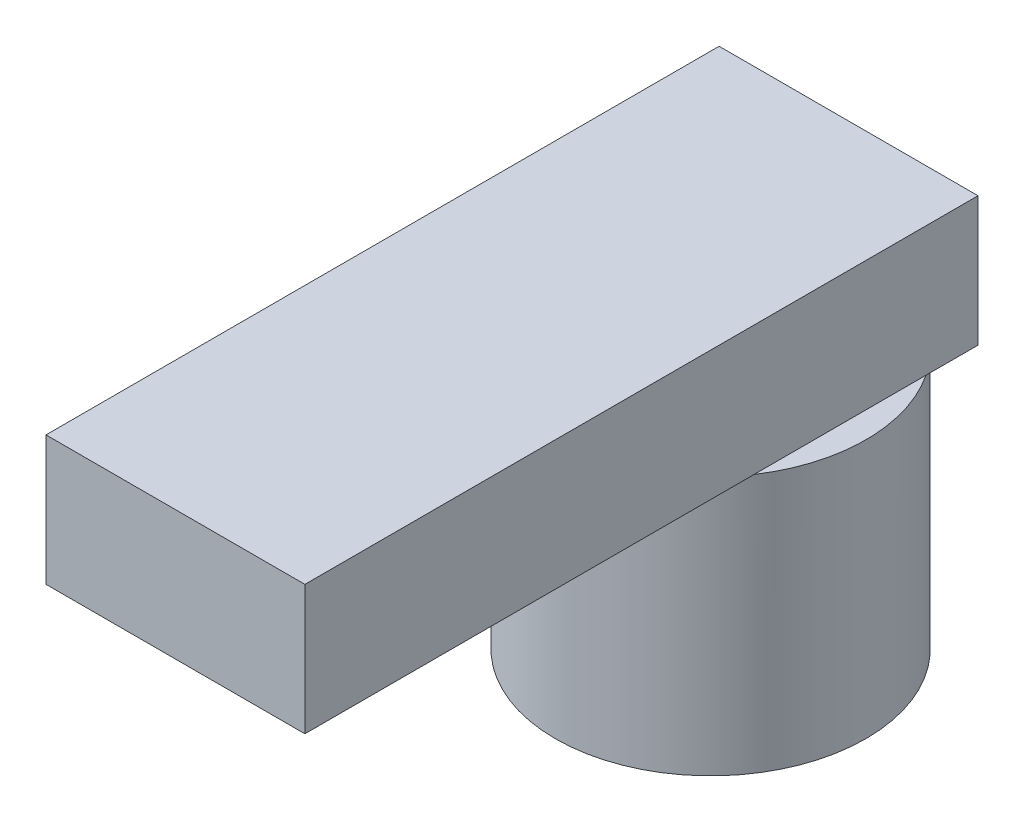
SolidWorks part; units mm, degrees
ref_plane "Front Plane" through (0, 0, 0) normal (0, 0, 1) x (1, 0, 0)
ref_plane "Top Plane" through (0, 0, 0) normal (0, 1, 0) x (1, 0, 0)
ref_plane "Right Plane" through (0, 0, 0) normal (1, 0, 0) x (0, 0, -1)
sketch "Sketch1" plane through (0, 0, 0) normal (0, 1, 0) x (1, 0, 0)
  line L1 (0, 0) -> (5, 0)
  line L2 (0, 0) -> (0, 13)
  line L3 (0, 13) -> (5, 13)
  line L4 (5, 0) -> (5, 13)
  dimension "D1" = 5
  dimension "D2" = 13
extrude "Boss-Extrude1" add sketch "Sketch1" along normal blind 2.5
sketch "Sketch2" plane through (0, 0, 0) normal (0, 1, 0) x (1, 0, 0)
  line L1 (5, 13) -> (0, 13) construction
  line L2 (2.5, 13) -> (2.5, 0) construction
  line L3 (0, 0) -> (5, 0) construction
  circle A0 centre (2.5, 10.3357) radius 3
  point P2 (0, 0)
  dimension "D1" = 6
extrude "Boss-Extrude2" add sketch "Sketch2" against normal blind 5
